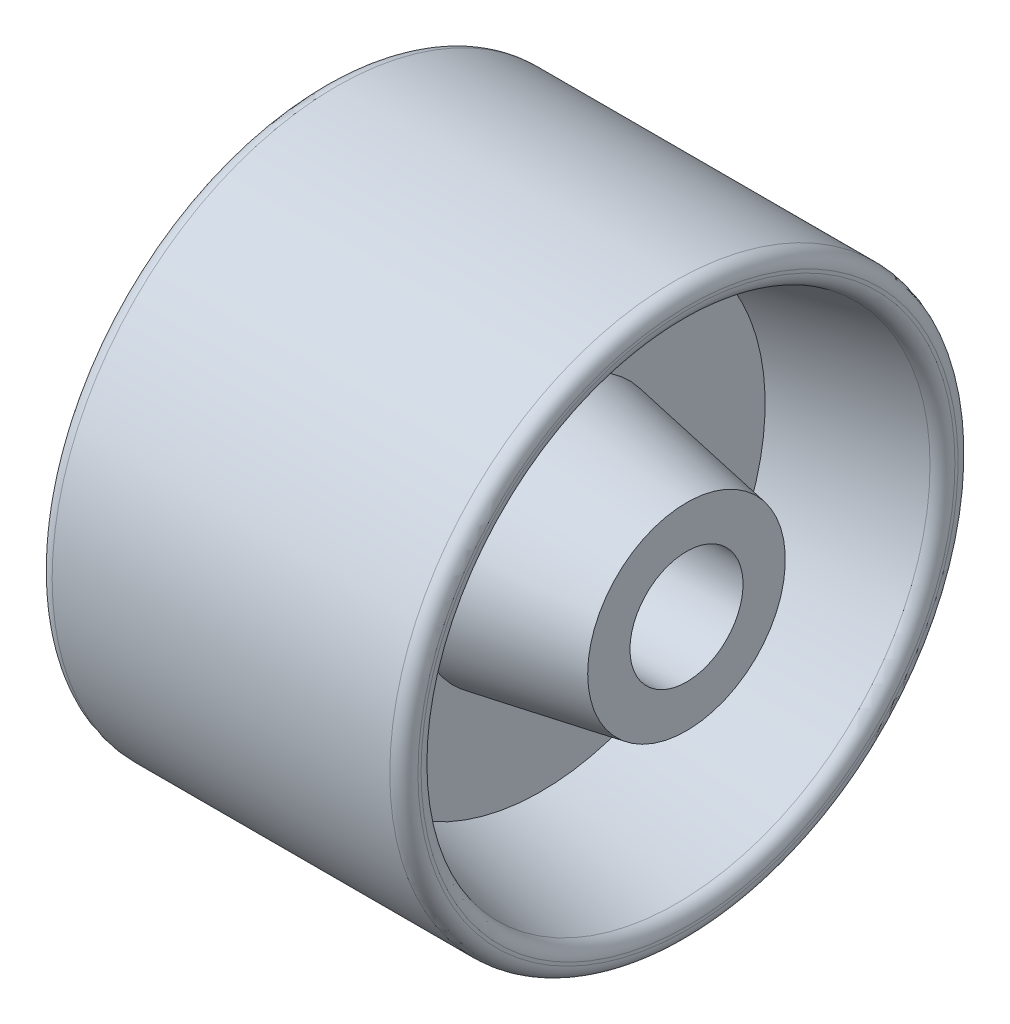
SolidWorks part; units mm, degrees
ref_plane "Front Plane" through (0, 0, 0) normal (0, 0, 1) x (1, 0, 0)
ref_plane "Top Plane" through (0, 0, 0) normal (0, 1, 0) x (1, 0, 0)
ref_plane "Right Plane" through (0, 0, 0) normal (1, 0, 0) x (0, 0, -1)
sketch "Sketch1" plane through (0, 0, 0) normal (0, 0, 1) x (1, 0, 0)
  line L0 (0, 121.4006) -> (0, -100.3473) construction
  line L1 (-142.9716, 0) -> (162.4798, 0) construction
  line L3 (64.4067, 20.0743) -> (64.4067, 35.0872)
  line L13 (-64.4067, 20.0743) -> (-64.4067, 35.0872)
  line L20 (64.4067, 20.0743) -> (-64.4067, 20.0743)
  line L21 (-64.4067, 35.0872) -> (-12.8274, 44.182)
  line L22 (64.4067, 35.0872) -> (12.8274, 44.182)
  line L23 (-12.8274, 79.5029) -> (-12.8274, 44.182)
  line L24 (12.8274, 79.5029) -> (12.8274, 44.182)
  line L25 (12.8274, 79.5029) -> (64.9385, 90.7268)
  line L26 (-12.8274, 79.5029) -> (-64.9385, 90.7268)
  line L27 (64.9385, 90.7268) -> (64.9385, 100.8778)
  line L28 (64.9385, 100.8778) -> (-64.9385, 100.8778)
  line L29 (-64.9385, 90.7268) -> (-64.9385, 100.8778)
  point P15 (0, 90.7268)
  point P20 (0, 23.9177)
  point P22 (0, 79.5029)
  dimension "D1" = 100
revolve "Revolve1" add sketch "Sketch1" angle 360 about L1
fillet "Fillet1" radius 5 1 edges at (-64.9385, 0, 100.8778)
fillet "Fillet2" radius 5 2 edges at (64.9385, 0, 90.7268) (64.9385, 0, 100.8778)
fillet "Fillet3" radius 5 1 edges at (-64.9385, 0, 90.7268)
